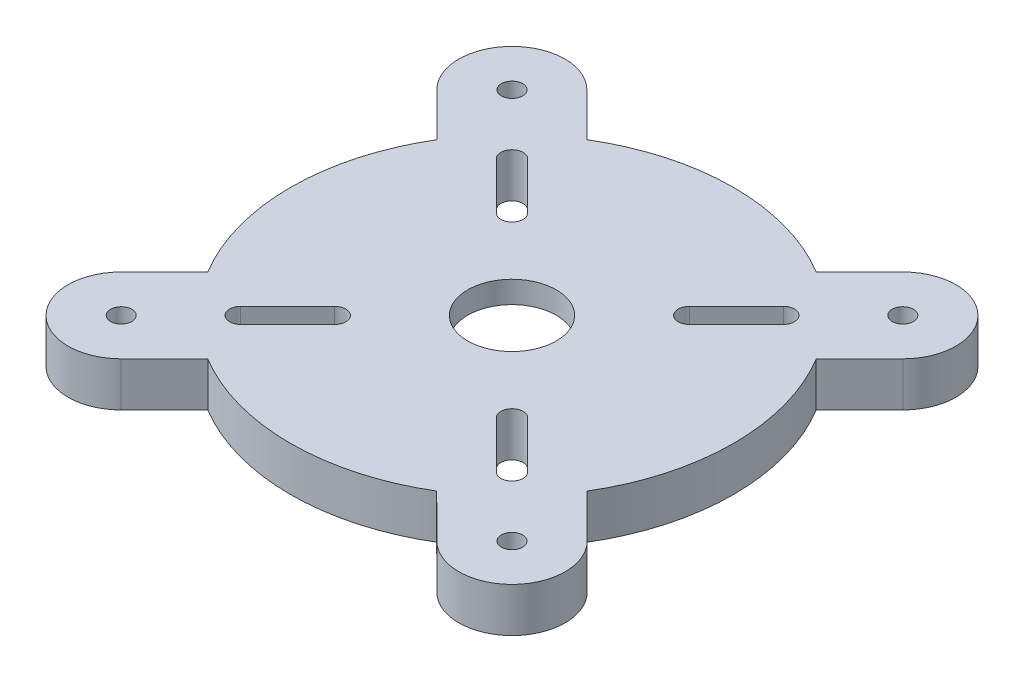
SolidWorks part; units mm, degrees
ref_plane "Front Plane" through (0, 0, 0) normal (0, 0, 1) x (1, 0, 0)
ref_plane "Top Plane" through (0, 0, 0) normal (0, 1, 0) x (1, 0, 0)
ref_plane "Right Plane" through (0, 0, 0) normal (1, 0, 0) x (0, 0, -1)
sketch "Sketch2" plane through (0, 0, 0) normal (0, 1, 0) x (1, 0, 0)
  line L0 (-35.8174, -35.8174) -> (44.0857, 44.0857) construction
  line L3 (-44.3027, -27.3321) -> (35.6004, 52.571)
  line L4 (-27.3321, -44.3027) -> (52.571, 35.6004)
  line L5 (4.1341, 4.1341) -> (135.9897, 4.1341) construction
  line L6 (0, 0) -> (0, 50) construction
  line L8 (35.8174, -35.8174) -> (-44.0857, 44.0857) construction
  line L9 (44.3027, -27.3321) -> (-35.6004, 52.571)
  line L10 (27.3321, -44.3027) -> (-52.571, 35.6004)
  line L11 (44.0857, 44.0857) -> (59.3318, 59.3318) construction
  line L12 (20, 20) -> (30.6066, 30.6066) construction
  line L13 (18.2322, 21.7678) -> (28.8388, 32.3744)
  line L14 (21.7678, 18.2322) -> (32.3744, 28.8388)
  line L15 (-35.8174, 35.8174) -> (44.0857, -44.0857) construction
  line L16 (-27.3321, 44.3027) -> (52.571, -35.6004)
  line L17 (-44.3027, 27.3321) -> (35.6004, -52.571)
  line L18 (35.8174, 35.8174) -> (-44.0857, -44.0857) construction
  line L19 (44.3027, 27.3321) -> (-35.6004, -52.571)
  line L20 (27.3321, 44.3027) -> (-52.571, -35.6004)
  line L21 (35.7319, -35.8174) -> (-44.1712, 44.0857) construction
  line L22 (27.2466, -44.3027) -> (-52.6565, 35.6004)
  line L23 (44.2172, -27.3321) -> (-35.6859, 52.571)
  line L24 (20, -20) -> (30.6066, -30.6066) construction
  line L25 (21.7678, -18.2322) -> (32.3744, -28.8388)
  line L26 (18.2322, -21.7678) -> (28.8388, -32.3744)
  line L27 (-20, -20) -> (-30.6066, -30.6066) construction
  line L28 (-18.2322, -21.7678) -> (-28.8388, -32.3744)
  line L29 (-21.7678, -18.2322) -> (-32.3744, -28.8388)
  line L30 (-20, 20) -> (-30.6066, 30.6066) construction
  line L31 (-21.7678, 18.2322) -> (-32.3744, 28.8388)
  line L32 (-18.2322, 21.7678) -> (-28.8388, 32.3744)
  circle A0 centre (0, 0) radius 50
  arc A3 (-44.3027, -27.3321) -> (-27.3321, -44.3027) centre (-35.8174, -35.8174) ccw
  arc A4 (52.571, 35.6004) -> (35.6004, 52.571) centre (44.0857, 44.0857) ccw
  arc A6 (-52.571, 35.6004) -> (-35.6004, 52.571) centre (-44.0857, 44.0857) cw
  arc A7 (35.6004, 52.571) -> (15.2219, 47.6266) centre (21.355, 66.8163) cw
  arc A8 (52.571, 35.6004) -> (47.6266, 15.2219) centre (66.8163, 21.355) ccw
  circle A9 centre (44.0857, 44.0857) radius 2.4
  arc A10 (18.2322, 21.7678) -> (21.7678, 18.2322) centre (20, 20) ccw
  arc A11 (32.3744, 28.8388) -> (28.8388, 32.3744) centre (30.6066, 30.6066) ccw
  circle A12 centre (44.0884, -44.0884) radius 2.4
  arc A13 (52.571, -35.6004) -> (47.6266, -15.2219) centre (66.8163, -21.355) cw
  arc A14 (35.6004, -52.571) -> (15.2219, -47.6266) centre (21.355, -66.8163) ccw
  arc A15 (-27.3321, 44.3027) -> (-44.3027, 27.3321) centre (-35.8174, 35.8174) ccw
  arc A16 (35.6004, -52.571) -> (52.571, -35.6004) centre (44.0857, -44.0857) ccw
  circle A17 centre (-44.0857, -44.0857) radius 2.4
  arc A18 (-35.6004, -52.571) -> (-15.2219, -47.6266) centre (-21.355, -66.8163) cw
  arc A19 (-52.571, -35.6004) -> (-47.6266, -15.2219) centre (-66.8163, -21.355) ccw
  arc A20 (44.3027, 27.3321) -> (27.3321, 44.3027) centre (35.8174, 35.8174) ccw
  arc A21 (-52.571, -35.6004) -> (-35.6004, -52.571) centre (-44.0857, -44.0857) ccw
  circle A22 centre (-44.0857, 44.0857) radius 2.4
  arc A23 (-52.6565, 35.6004) -> (-47.6266, 15.2219) centre (-66.8368, 21.2904) cw
  arc A24 (-35.6004, 52.571) -> (-15.2219, 47.6266) centre (-21.355, 66.8163) ccw
  arc A25 (27.2466, -44.3027) -> (28.1401, -45.1107) centre (35.7319, -35.8174) ccw
  arc A26 (-35.6859, 52.571) -> (-52.6565, 35.6004) centre (-44.1712, 44.0857) ccw
  arc A27 (21.7678, -18.2322) -> (18.2322, -21.7678) centre (20, -20) ccw
  arc A28 (28.8388, -32.3744) -> (32.3744, -28.8388) centre (30.6066, -30.6066) ccw
  arc A29 (-18.2322, -21.7678) -> (-21.7678, -18.2322) centre (-20, -20) ccw
  arc A30 (-32.3744, -28.8388) -> (-28.8388, -32.3744) centre (-30.6066, -30.6066) ccw
  arc A31 (-21.7678, 18.2322) -> (-18.2322, 21.7678) centre (-20, 20) ccw
  arc A32 (-28.8388, 32.3744) -> (-32.3744, 28.8388) centre (-30.6066, 30.6066) ccw
  point P3 (4.1341, 4.1341)
  point P15 (-4.1341, 4.1341)
  point P30 (25.3033, 25.3033)
  point P38 (4.1341, -4.1341)
  point P52 (-4.1341, -4.1341)
  point P66 (-4.2197, 4.1341)
  point P80 (0, 0)
  point P83 (25.3033, -25.3033)
  point P90 (-25.3033, -25.3033)
  point P97 (-25.3033, 25.3033)
  point P102 (0, 0)
  dimension "D1" = 45
  dimension "D3" = 12
  dimension "D4" = 2.5
  dimension "D2" = 113
  dimension "D5" = 15
  dimension "D6" = 20
  dimension "D8" = 4
extrude "Boss-Extrude1" add sketch "Sketch2" along normal blind 10
sketch "Sketch3" plane through (0, 0, 0) normal (0, -1, 0) x (-1, 0, 0)
  circle A0 centre (0, 0) radius 22
  circle A1 centre (0, -14.5) radius 1.75
  circle A2 centre (-12.5574, 7.25) radius 1.75
  circle A3 centre (12.5574, 7.25) radius 1.75
  point P11 (0, 0)
  dimension "D1" = 3.5
  dimension "D3" = 3
  dimension "D2" = 14.5
extrude "Cut-Extrude1" cut sketch "Sketch3" against normal blind 5.03 contours A0
sketch "Sketch4" plane through (0, 5.03, 0) normal (0, -1, 0) x (1, 0, 0)
  circle A0 centre (0, 14.9531) radius 1.75
  circle A1 centre (12.9498, -7.4765) radius 1.75
  circle A2 centre (-12.9498, -7.4765) radius 1.75
  point P8 (0, 0)
  dimension "D1" = 3
extrude "Cut-Extrude3" [suppressed] cut sketch "Sketch4" against normal blind 5.03 contours A0 | A2 | A1
sketch "Sketch5" plane through (0, 10, 0) normal (0, 1, 0) x (1, 0, 0)
  circle A0 centre (0, 0) radius 10
extrude "Cut-Extrude4" cut sketch "Sketch5" against normal blind 5.03
